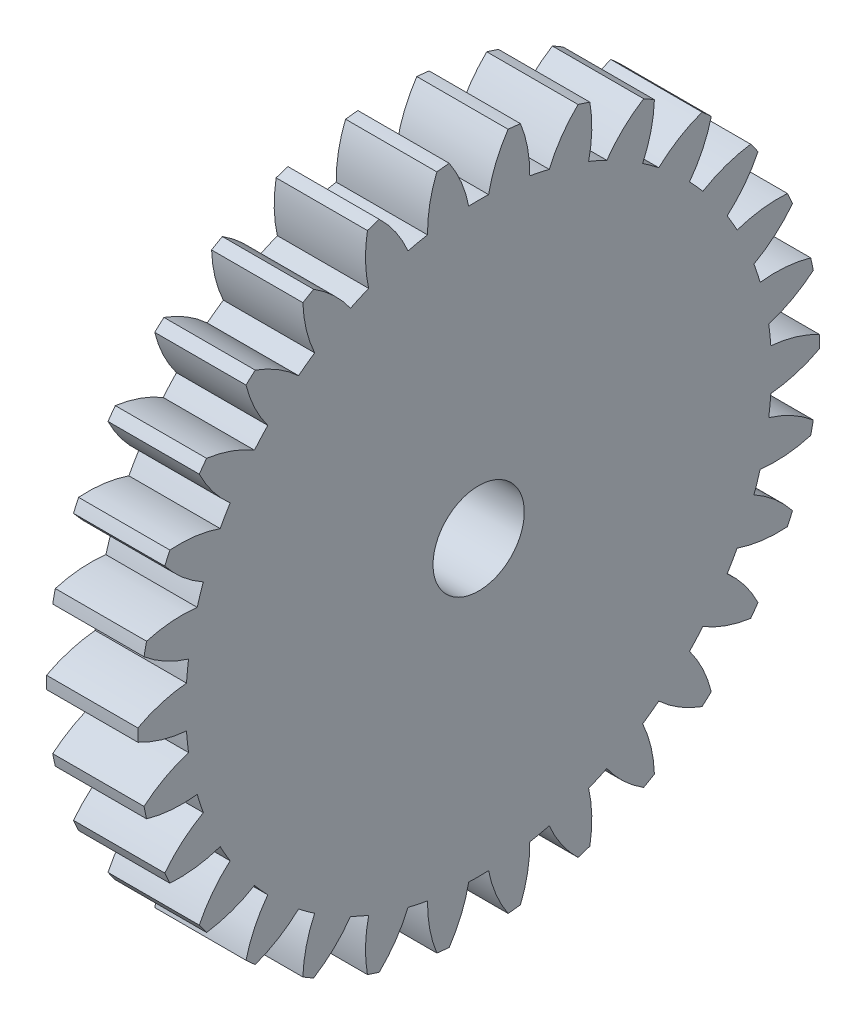
SolidWorks part; units mm, degrees
ref_plane "Plane1" through (0, 0, 0) normal (0, 0, 1) x (1, 0, 0)
ref_plane "Plane2" through (0, 0, 0) normal (0, 1, 0) x (1, 0, 0)
ref_plane "Plane3" through (0, 0, 0) normal (1, 0, 0) x (0, 0, -1)
sketch "HoldingSke" plane through (0, 0, 0) normal (0, 1, 0) x (1, 0, 0)
  line L0 (0, 0) -> (1.2372, -0.7143)
  line L1 (-15, 0) -> (100, 0) construction
  line L2 (0, 0) -> (-2.1039, 2.3779)
  line L3 (0, 0) -> (-11.863, 4.5341)
  line L4 (0, 0) -> (7.479, 4.318)
  line L5 (0, 0) -> (-46.8476, -17.4728)
  line L6 (0, 0) -> (-2.4869, -1.6779)
  line L7 (-2.1039, 2.3779) -> (8.6586, 51.2059)
  line L8 (-76.2, 54.61) -> (-75.7, 54.61)
  line L9 (-71.009, 38.7566) -> (-53.1078, 45.2721)
  line L10 (-76.2, 71.12) -> (104.1128, 71.12)
  line L11 (0, 0) -> (-3, 0)
  line L12 (-76.2, 101.6) -> (-76.173, 101.6)
  line L13 (24.9733, 27.94) -> (52.9518, 28.4284)
  line L14 (24.9733, 27.94) -> (24.9743, 27.94)
  line L15 (24.9733, 27.94) -> (100.4006, 29.5858)
  line L16 (-63.627, -0.7) -> (-12.827, -0.7)
  circle A0 centre (0, 0) radius 1.5
  circle A1 centre (0, 0) radius 9.624
  circle A2 centre (0, 0) radius 37.5
  circle A3 centre (0, 0) radius 1.5
  dimension "MHD" = 19.248
  dimension "Hub_dia" = 75
  dimension "Bore" = 3
  dimension "MBD" = 3
  dimension "Num_teeth" = 30
  dimension "Pitch" = 1.4286
  dimension "Overall_len" = 50
  dimension "Show_teeth" = 30
  dimension "Thickness" = 3
  dimension "OAL" = 50.0001
  dimension "T_dim" = 0.5
  dimension "Ap" = 20
  dimension "H" = 19.05
  dimension "Pitch_radius" = 180.3128
  dimension "Width" = 3
  dimension "Backlash" = 0.027
  dimension "Addendum_fac" = 1
  dimension "Dedendum_fac" = 1.25
  dimension "Clearance_fac" = 0.25
  dimension "Dedendum_add" = 0.001
  dimension "Module" = 0.7
sketch "BasProSke" plane through (0, 0, 0) normal (0, 1, 0) x (1, 0, 0)
  line L0 (-10, 0) -> (60, 0) construction
  line L1 (0, 0) -> (0, 11.2)
  line L2 (0, 0) -> (3, 0)
  line L3 (3, 0) -> (3, 11.2)
  line L4 (3, 11.2) -> (0, 11.2)
  dimension "Thickness" = 3
  dimension "Diameter" = 22.4
revolve "Base-Revolve" add sketch "BasProSke" angle 360 about L0
sketch "TooCutSke" plane through (0, 0, 0) normal (1, 0, 0) x (0, 0, -1)
  line L1 (0, 0) -> (0, 107) construction
  line L2 (0, 0) -> (-0.5968, 10.483) construction
  line L3 (0, 0) -> (-2.1926, 20.8611) construction
  line L4 (-0.5968, 10.483) -> (-1.0963, 10.4305) construction
  arc A0 (0.3271, 9.6184) -> (-0.3271, 9.6184) centre (0, 0) ccw
  arc A1 (0.9839, 11.1822) -> (-0.9839, 11.1822) centre (0, 0) ccw
  circle A2 centre (0, 0) radius 10.5 construction
  circle A3 centre (0, 0) radius 9.8668 construction
  arc A4 (-0.3271, 9.6184) -> (-0.9839, 11.1822) centre (-4.448, 8.8073) ccw
  arc A5 (0.9839, 11.1822) -> (0.3271, 9.6184) centre (4.448, 8.8073) ccw
  dimension "Root_dia" = 19.248
  dimension "Overcut_dia" = 22.4508
  dimension "Pitch_dia" = 21
  dimension "Base_dia" = 19.7335
  dimension "Flank_rad" = 4.2
  dimension "Half_ang" = 6
  dimension "Half_CT" = 0.5023
extrude "ToothCut" cut sketch "TooCutSke" along normal through all
fillet "Breaks" [suppressed] radius 0.014
fillet "RootFillets" [suppressed] radius 0.176
pattern_circular "TeethCuts" count 30 every 12 about axis through (-10, 0, 0) along (1, 0, 0) of "ToothCut", "RootFillets", "Breaks"
sketch "HubNeaOneSke" plane through (0, 0, 0) normal (-1, 0, 0) x (0, 0, 1)
  circle A0 centre (0, 0) radius 9.624
  dimension "Diameter" = 19.248
extrude "HubNearOne" [suppressed] add sketch "HubNeaOneSke" along normal blind 47.0001
sketch "HubNeaBotSke" plane through (0, 0, 0) normal (-1, 0, 0) x (0, 0, 1)
  circle A0 centre (0, 0) radius 9.624
  dimension "Diameter" = 19.248
extrude "HubNearBoth" [suppressed] add sketch "HubNeaBotSke" along normal blind 23.5
ref_plane "FarPln" through (3, 0, 0) normal (1, 0, 0) x (0, 0, -1)
sketch "HubFarSke" plane through (3, 0, 0) normal (1, 0, 0) x (0, 0, -1)
  circle A0 centre (0, 0) radius 9.624
  dimension "Diameter" = 19.248
extrude "HubFar" [suppressed] add sketch "HubFarSke" along normal blind 23.5
sketch "BorSke" plane through (0, 0, 0) normal (1, 0, 0) x (0, 0, -1)
  circle A0 centre (0, 0) radius 1.5
  dimension "Diameter" = 3
extrude "Bore" cut sketch "BorSke" along normal mid plane 100.0001
sketch "KeySke" plane through (0, 0, 0) normal (1, 0, 0) x (0, 0, -1)
  line L0 (-0.6, 0) -> (-0.6, 2)
  line L1 (-0.6, 2) -> (0.6, 2)
  line L2 (0.6, 2) -> (0.6, 0)
  line L3 (0, 0) -> (0, 34) construction
  line L4 (-0.6, 0) -> (0.6, 0)
  dimension "Offset" = 2
  dimension "Width" = 1.2
extrude "Keyway" [suppressed] cut sketch "KeySke" along normal mid plane 100.0001
pattern_circular "Keyway2" [suppressed] count 2 every 90 about axis through (-10, 0, 0) along (1, 0, 0)
equation "' \"Module@HoldingSke\" = 6.35"
equation "' \"Num_teeth@HoldingSke\" = 12"
equation "' \"Ap@HoldingSke\" =  20"
equation "' \"Ap@HoldingSke\" = 20"
equation "' \"Width@HoldingSke\" = 0.5 * 25.4"
equation "' \"Hub_dia@HoldingSke\"= 1 * 25.4"
equation "' \"Hub_dia@HoldingSke\" = 1 * 25.4"
equation "' \"Overall_len@HoldingSke\" = 1.0 * 25.4"
equation "' \"Bore@HoldingSke\" = 0.75 * 25.4"
equation "' \"T_dim@HoldingSke\" = 0.1 * 25.4"
equation "' \"Width@KeySke\" = 0.25 * 25.4"
equation "' \"Show_teeth@HoldingSke\" = 13"
equation "' \"Backlash@HoldingSke\" = 0.009 * 25.4"
equation "' \"Addendum_fac@HoldingSke\" = 1.0"
equation "' \"Dedendum_fac@HoldingSke\" = 1.25"
equation "' \"Dedendum_add@HoldingSke\" = 0.00005 * 25.4"
equation "' \"Clearance_fac@HoldingSke\" = 0.25"
equation "\"Pitch@HoldingSke\" = 1 / \"Module@HoldingSke\""
equation "\"Overcut_dia@TooCutSke\" = (\"Num_teeth@HoldingSke\" + 2 * \"Addendum_fac@HoldingSke\") / \"Pitch@HoldingSke\" + 0.002 * 25.4"
equation "\"Pitch_dia@TooCutSke\" = \"Num_teeth@HoldingSke\" / \"Pitch@HoldingSke\""
equation "\"Base_dia@TooCutSke\" = \"Num_teeth@HoldingSke\" / \"Pitch@HoldingSke\" * cos((\"Ap@HoldingSke\"  * 3.14159265 / 180))"
equation "\"Root_dia@TooCutSke\" = (\"Num_teeth@HoldingSke\" + 2) / \"Pitch@HoldingSke\" - 2 * (\"Addendum_fac@HoldingSke\" + \"Dedendum_fac@HoldingSke\") / \"Pitch@HoldingSke\" - \"Dedendum_add@HoldingSke\" * 2"
equation "\"Half_ang@TooCutSke\" = 180 / \"Num_teeth@HoldingSke\""
equation "\"Half_CT@TooCutSke\" = \"Num_teeth@HoldingSke\" / \"Pitch@HoldingSke\" * sin((3.14159265 / 2 / \"Num_teeth@HoldingSke\")) / 2 - 7 * \"Backlash@HoldingSke\" / 4"
equation "\"Flank_rad@TooCutSke\" = \"Num_teeth@HoldingSke\" / \"Pitch@HoldingSke\" / 5"
equation "\"Radius@RootFillets\" = \"Clearance_fac@HoldingSke\" / \"Pitch@HoldingSke\" + \"Dedendum_add@HoldingSke\""
equation "\"Break_rad@Breaks\" = 0.02 / \"Pitch@HoldingSke\""
equation "\"Thickness@HoldingSke\" = \"Width@HoldingSke\""
equation "\"OAL@HoldingSke\" = \"Thickness@HoldingSke\""
equation "\"MHD@HoldingSke\" = (\"Num_teeth@HoldingSke\" + 2) / \"Pitch@HoldingSke\" - 2 * (\"Addendum_fac@HoldingSke\" + \"Dedendum_fac@HoldingSke\")  / \"Pitch@HoldingSke\" - \"Dedendum_add@HoldingSke\" * 2"
equation "\"MBD@HoldingSke\" = (\"Num_teeth@HoldingSke\" + 2) / \"Pitch@HoldingSke\" - 2 * (\"Addendum_fac@HoldingSke\" + \"Dedendum_fac@HoldingSke\")  / \"Pitch@HoldingSke\" - \"Dedendum_add@HoldingSke\" * 2 - 0.002 * 25.4"
equation "\"MHD@HoldingSke\" = ((sgn( \"MHD@HoldingSke\" - \"Hub_dia@HoldingSke\" )-1)*( \"MHD@HoldingSke\" - \"Hub_dia@HoldingSke\" ))/-2+ \"Hub_dia@HoldingSke\""
equation "\"MBD@HoldingSke\" = ((sgn( \"MBD@HoldingSke\" - \"Bore@HoldingSke\" )-1)*( \"MBD@HoldingSke\" - \"Bore@HoldingSke\" ))/-2+ \"Bore@HoldingSke\""
equation "\"OAL@HoldingSke\" = ((sgn( \"OAL@HoldingSke\" - \"Overall_len@HoldingSke\" )+1)*( \"OAL@HoldingSke\" - \"Overall_len@HoldingSke\" ))/2 + \"Overall_len@HoldingSke\" + 0.000002 * 25.4"
equation "\"Num_teeth@TeethCuts\" = int( \"Show_teeth@HoldingSke\" ) + 1"
equation "\"Num_teeth@TeethCuts\" = ((sgn( \"Num_teeth@TeethCuts\" - \"Num_teeth@HoldingSke\" )-1)*( \"Num_teeth@TeethCuts\" - \"Num_teeth@HoldingSke\" ))/-2+ \"Num_teeth@HoldingSke\""
equation "\"Num_teeth@TeethCuts\" = ((sgn( \"Num_teeth@TeethCuts\" - 2.0)+1)*( \"Num_teeth@TeethCuts\" - 2.0))/2 +2.0"
equation "\"Angle@TeethCuts\" = 360.0 / \"Num_teeth@HoldingSke\""
equation "\"Diameter@BasProSke\" = (\"Num_teeth@HoldingSke\" + 2 * \"Addendum_fac@HoldingSke\") / \"Pitch@HoldingSke\""
equation "\"Thickness@BasProSke\"  = \"Thickness@HoldingSke\""
equation "' \"Fillet_rad@BasProSke\" =  \"Thickness@HoldingSke\" * 0.05"
equation "' \"Fillet_rad@BasProSke\" = \"Thickness@HoldingSke\" * 0.05"
equation "\"MHD@HoldingSke\" = ((sgn( \"MHD@HoldingSke\" - \"Root_dia@TooCutSke\" )-1)*( \"MHD@HoldingSke\" - \"Root_dia@TooCutSke\" ))/-2+ \"Root_dia@TooCutSke\""
equation "\"Diameter@HubNeaOneSke\" = \"MHD@HoldingSke\""
equation "\"Length@HubNearOne\" = \"OAL@HoldingSke\" - \"Thickness@BasProSke\""
equation "\"Diameter@HubNeaBotSke\" = \"MHD@HoldingSke\""
equation "\"Length@HubNearBoth\" = ( \"OAL@HoldingSke\" - \"Thickness@BasProSke\" ) / 2.0"
equation "\"Thickness@FarPln\" = \"Thickness@BasProSke\""
equation "\"Diameter@HubFarSke\" = \"MHD@HoldingSke\""
equation "\"Length@HubFar\" = ( \"OAL@HoldingSke\" - \"Thickness@BasProSke\" ) / 2.0"
equation "\"Diameter@BorSke\" = \"MBD@HoldingSke\""
equation "\"D1@Bore\" = \"OAL@HoldingSke\" * 2.0"
equation "\"D1@Keyway\" = \"OAL@HoldingSke\" * 2.0"
equation "\"Offset@KeySke\" = \"T_dim@HoldingSke\" + \"MBD@HoldingSke\" / 2.0"
